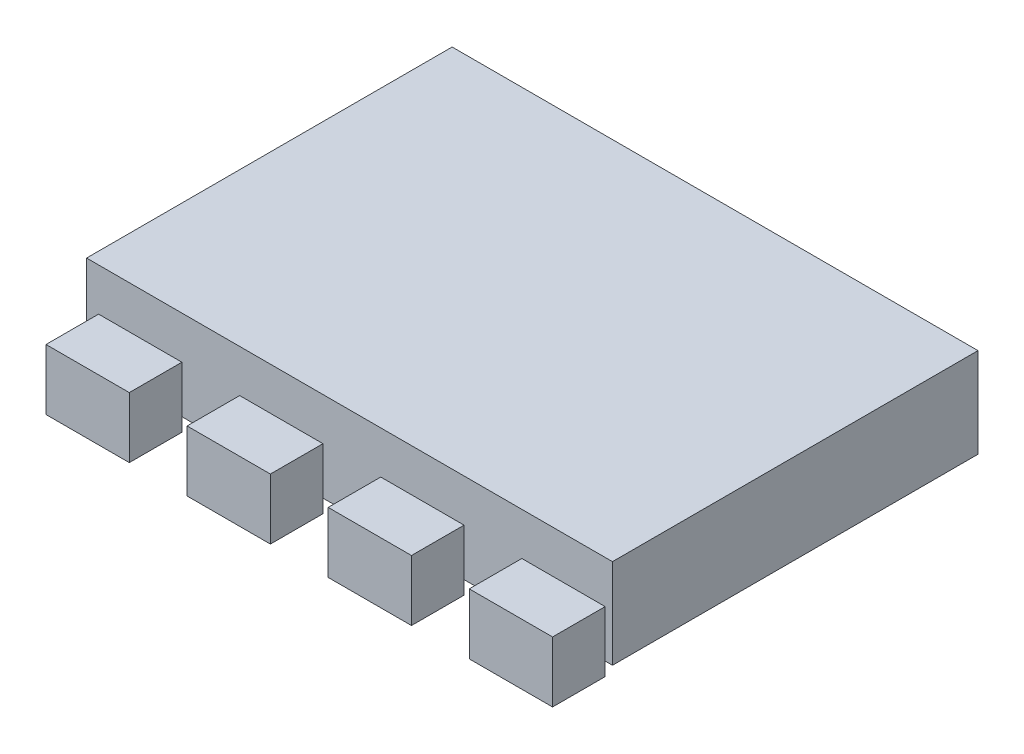
SolidWorks part; units mm, degrees
ref_plane "前视基准面" through (0, 0, 0) normal (0, 0, 1) x (1, 0, 0)
ref_plane "上视基准面" through (0, 0, 0) normal (0, 1, 0) x (1, 0, 0)
ref_plane "右视基准面" through (0, 0, 0) normal (1, 0, 0) x (0, 0, -1)
sketch "草图1" plane through (0, 0, 0) normal (0, 1, 0) x (1, 0, 0)
  line L1 (-41, -28.5) -> (41, -28.5)
  line L2 (-41, -28.5) -> (-41, 28.5)
  line L3 (-41, 28.5) -> (41, 28.5)
  line L4 (41, -28.5) -> (41, 28.5)
  line L5 (-41, -28.5) -> (41, 28.5) construction
  line L6 (-41, 28.5) -> (41, -28.5) construction
  point P0 (0, 0)
  dimension "D1" = 82
  dimension "D2" = 57
extrude "凸台-拉伸1" add sketch "草图1" along normal blind 14
sketch "草图2" plane through (0, 0, 28.5) normal (0, 0, 1) x (1, 0, 0)
  line L1 (-39.1299, -2.1009) -> (-26.1401, -2.1009)
  line L2 (-39.1299, -2.1009) -> (-39.1299, 7.3608)
  line L3 (-39.1299, 7.3608) -> (-26.1401, 7.3608)
  line L4 (-26.1401, -2.1009) -> (-26.1401, 7.3608)
  line L5 (-39.1299, -2.1009) -> (-26.1401, 7.3608) construction
  line L6 (-39.1299, 7.3608) -> (-26.1401, -2.1009) construction
  point P0 (-32.635, 2.63)
extrude "凸台-拉伸2" add sketch "草图2" along normal blind 8.2
pattern_linear "阵列(线性)1" count 4 spacing 22 along (1, 0, 0) of "凸台-拉伸2"
